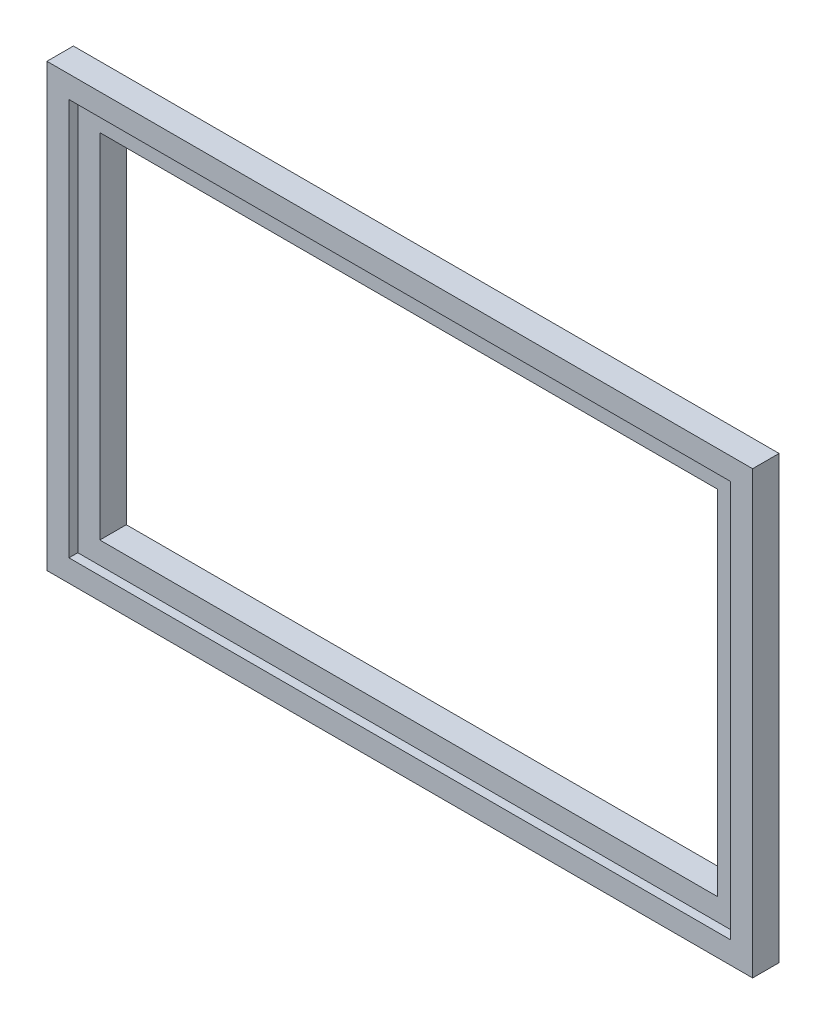
SolidWorks part; units mm, degrees
ref_plane "정면" through (0, 0, 0) normal (0, 0, 1) x (1, 0, 0)
ref_plane "윗면" through (0, 0, 0) normal (0, 1, 0) x (1, 0, 0)
ref_plane "우측면" through (0, 0, 0) normal (1, 0, 0) x (0, 0, -1)
sketch "스케치1" plane through (0, 0, 0) normal (0, 0, 1) x (1, 0, 0)
  line L28 (-77.5, 2.5) -> (-2.5, 2.5)
  line L29 (-2.5, 2.5) -> (-2.5, 47.5)
  line L30 (-2.5, 47.5) -> (-77.5, 47.5)
  line L31 (-77.5, 47.5) -> (-77.5, 2.5)
  line L32 (-80, 0) -> (0, 0)
  line L33 (0, 0) -> (0, 50)
  line L34 (0, 50) -> (-80, 50)
  line L35 (-80, 50) -> (-80, 0)
  line L36 (-77.5, 2.5) -> (-2.5, 2.5)
  line L37 (-2.5, 2.5) -> (-2.5, 47.5)
  line L38 (-2.5, 47.5) -> (-77.5, 47.5)
  line L39 (-77.5, 47.5) -> (-77.5, 2.5)
  line L40 (-75, 5) -> (-5, 5)
  line L41 (-5, 5) -> (-5, 45)
  line L42 (-5, 45) -> (-75, 45)
  line L43 (-75, 45) -> (-75, 5)
  dimension "D1" = 50
  dimension "D2" = 80
  dimension "D3" = 77.5
  dimension "D4" = 47.5
  dimension "D5" = 45
  dimension "D6" = 75
  dimension "D7" = 2.5
  dimension "D8" = 2.5
  dimension "D9" = 2.5
  dimension "D10" = 2.5
extrude "보스-돌출1" add sketch "스케치1" along normal blind 2 contours L30 L31 L28 L29 L43 L42 L41 L40 | L34 L35 L32 L33 L31 L30 L29 L28
sketch "스케치2" plane through (0, 0, 2) normal (0, 0, 1) x (1, 0, 0)
  line L4 (-80, 0) -> (0, 0) construction
  line L5 (-80, 50) -> (-80, 0) construction
  line L6 (0, 50) -> (-80, 50) construction
  line L7 (0, 0) -> (0, 50) construction
  line L8 (-2.5, 47.5) -> (-77.5, 47.5)
  line L9 (-77.5, 47.5) -> (-77.5, 2.5)
  line L10 (-77.5, 2.5) -> (-2.5, 2.5)
  line L11 (-2.5, 2.5) -> (-2.5, 47.5)
  line L12 (-2.5, 47.5) -> (-77.5, 47.5)
  line L13 (-77.5, 47.5) -> (-77.5, 2.5)
  line L14 (-77.5, 2.5) -> (-2.5, 2.5)
  line L15 (-2.5, 2.5) -> (-2.5, 47.5)
  line L16 (-80, 0) -> (0, 0)
  line L17 (-80, 50) -> (-80, 0)
  line L18 (0, 50) -> (-80, 50)
  line L19 (0, 0) -> (0, 50)
  dimension "D1" = 2.5
extrude "보스-돌출2" add sketch "스케치2" along normal blind 1
sketch "스케치3" plane through (0, 0, 0) normal (0, 0, -1) x (-1, 0, 0)
  line L0 (2.5, 2.5) -> (77.5, 2.5)
  line L1 (77.5, 2.5) -> (77.5, 47.5)
  line L2 (77.5, 47.5) -> (2.5, 47.5)
  line L3 (2.5, 47.5) -> (2.5, 2.5)
  line L4 (80, 50) -> (0, 50)
  line L5 (0, 50) -> (0, 0)
  line L6 (0, 0) -> (80, 0)
  line L7 (80, 0) -> (80, 50)
  line L8 (80, 50) -> (0, 50)
  line L9 (0, 50) -> (0, 0)
  line L10 (0, 0) -> (80, 0)
  line L11 (80, 0) -> (80, 50)
  line L12 (75, 5) -> (5, 5) construction
  line L13 (5, 5) -> (5, 45) construction
  line L14 (5, 45) -> (75, 45) construction
  line L15 (75, 45) -> (75, 5) construction
  line L16 (75, 5) -> (5, 5)
  line L17 (5, 5) -> (5, 45)
  line L18 (5, 45) -> (75, 45)
  line L19 (75, 45) -> (75, 5)
  line M9 (75, 45) -> (75, 5)
  line M10 (75, 5) -> (5, 5)
  line M11 (5, 5) -> (5, 45)
  line M12 (5, 45) -> (75, 45)
  dimension "D1" = 0
  dimension "D2" = 2.5
extrude "보스-돌출3" add sketch "스케치3" along normal blind 1 contours L2 L3 L0 L1 M12 M9 M10 M11
